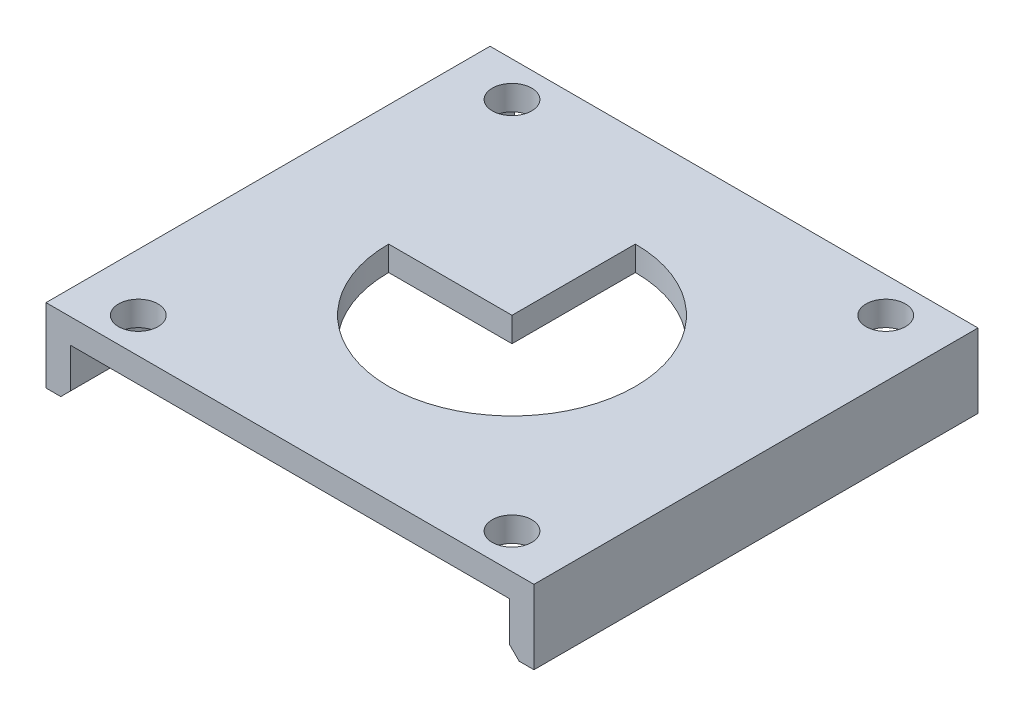
SolidWorks part; units mm, degrees
ref_plane "Front Plane" through (0, 0, 0) normal (0, 0, 1) x (1, 0, 0)
ref_plane "Top Plane" through (0, 0, 0) normal (0, 1, 0) x (1, 0, 0)
ref_plane "Right Plane" through (0, 0, 0) normal (1, 0, 0) x (0, 0, -1)
sketch "Sketch1" plane through (0, 0, 0) normal (0, 1, 0) x (1, 0, 0)
  line L0 (-37.875, 37.875) -> (37.875, -37.875) construction
  line L1 (-49.45, -45) -> (49.45, -45)
  line L2 (-49.45, -45) -> (-49.45, 45)
  line L3 (-49.45, 45) -> (49.45, 45)
  line L4 (49.45, -45) -> (49.45, 45)
  line L5 (-49.45, -45) -> (49.45, 45) construction
  line L6 (-49.45, 45) -> (49.45, -45) construction
  line L7 (0, 25) -> (0, 0)
  line L8 (0, 0) -> (-25, 0)
  circle A0 centre (0, 0) radius 25
  circle A1 centre (-37.875, 37.875) radius 4
  circle A2 centre (37.875, 37.875) radius 4
  circle A3 centre (-37.875, -37.875) radius 4
  circle A4 centre (37.875, -37.875) radius 4
  point P0 (0, 0)
  point P16 (0, 0)
  dimension "D2" = 50
  dimension "D3" = 8
  dimension "D4" = 75.75
  dimension "D1" = 98.9
  dimension "D5" = 75.75
  dimension "D6" = 90
extrude "Boss-Extrude1" add sketch "Sketch1" along normal blind 5 contours L1 L4 L3 L2 A4 A3 A2 A1 A0 | L7 A0 L8
sketch "Sketch2" plane through (0, 0, 0) normal (0, -1, 0) x (1, 0, 0)
  line L0 (-49.45, -45) -> (49.45, -45) construction
  line L1 (-49.45, 45) -> (-44.45, 45)
  line L2 (-49.45, 45) -> (-49.45, -45)
  line L3 (-49.45, -45) -> (-44.45, -45)
  line L4 (-44.45, 45) -> (-44.45, -45)
  line L6 (49.45, 45) -> (44.45, 45)
  line L7 (49.45, 45) -> (49.45, -45)
  line L8 (49.45, -45) -> (44.45, -45)
  line L9 (44.45, 45) -> (44.45, -45)
  dimension "D1" = 5
  dimension "D2" = 5
extrude "Boss-Extrude2" add sketch "Sketch2" along normal blind 10
chamfer "Chamfer1" distance 2 angle 45 2 edges at (44.45, -10, 0) (-44.45, -10, 0)
